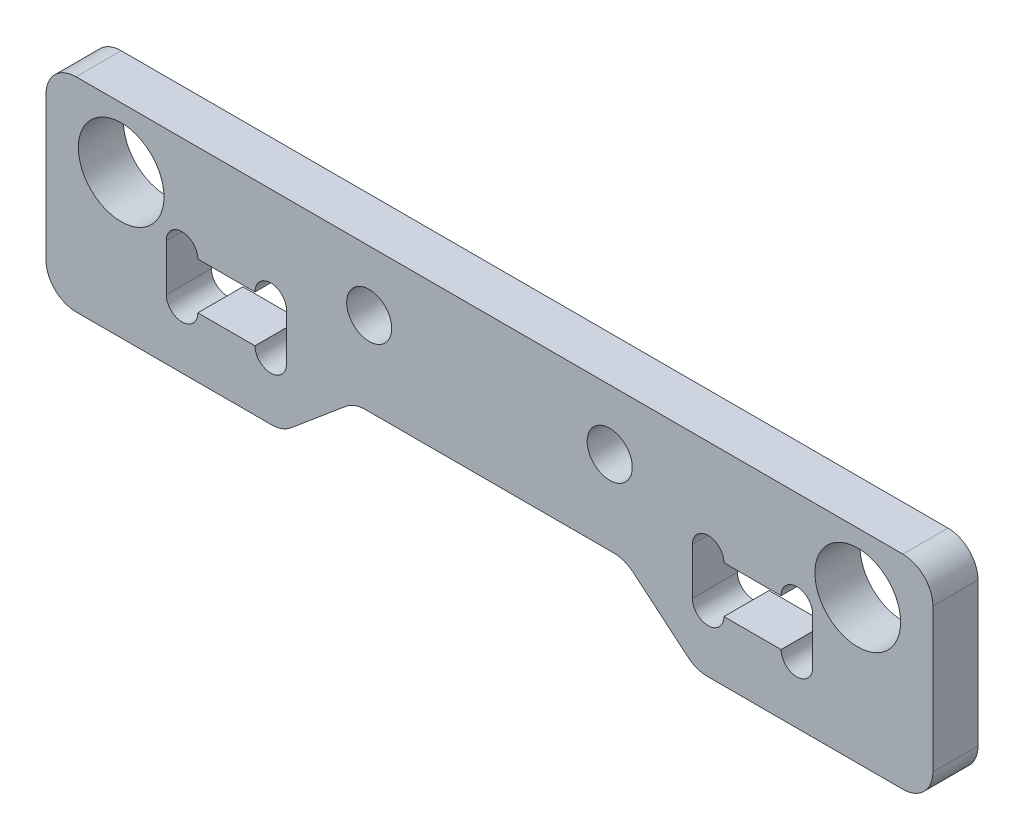
SolidWorks part; units mm, degrees
material "Thornel Mat VMA"
ref_plane "前视基准面" through (0, 0, 0) normal (0, 0, 1) x (1, 0, 0)
ref_plane "上视基准面" through (0, 0, 0) normal (0, 1, 0) x (1, 0, 0)
ref_plane "右视基准面" through (0, 0, 0) normal (1, 0, 0) x (0, 0, -1)
sketch "草图1" plane through (0, 0, 0) normal (0, 0, 1) x (1, 0, 0)
  line L0 (0, 0) -> (0, 24.7592) construction
  line L1 (-29.5, 4) -> (-29.5, -9.55)
  line L8 (-29.5, -9.55) -> (-13.767, -9.55)
  line L11 (29.5, -9.55) -> (29.5, 4)
  line L12 (29.5, 4) -> (-29.5, 4)
  line L13 (13.5, -2.45) -> (21.5, -2.45)
  line L14 (-13.5, -5.55) -> (-21.5, -5.55)
  line L15 (-13.5, -5.55) -> (-13.5, -2.45)
  line L16 (-13.5, -2.45) -> (-21.5, -2.45)
  line L17 (-21.5, -5.55) -> (-21.5, -2.45)
  line L18 (-13.5, -5.55) -> (-21.5, -2.45) construction
  line L19 (-13.5, -2.45) -> (-21.5, -5.55) construction
  line L20 (21.5, -5.55) -> (21.5, -2.45)
  line L21 (13.5, -5.55) -> (21.5, -5.55)
  line L22 (13.5, -5.55) -> (13.5, -2.45)
  line L23 (17.5, -2.45) -> (17.5, -4.5994) construction
  line L24 (-13.767, -9.55) -> (-9, -5.55)
  line L25 (-9, -5.55) -> (9, -5.55)
  line L26 (9, -5.55) -> (13.767, -9.55)
  line L27 (13.767, -9.55) -> (29.5, -9.55)
  circle A0 centre (-24.5, 0) radius 2.85
  circle A1 centre (24.5, 0) radius 2.85
  circle A6 centre (-8, 0) radius 1.5
  circle A7 centre (8, 0) radius 1.5
  circle A8 centre (-20.45, -2.45) radius 1.05
  circle A9 centre (-20.45, -5.55) radius 1.05
  circle A10 centre (-14.55, -2.45) radius 1.05
  circle A11 centre (-14.55, -5.55) radius 1.05
  circle A12 centre (14.55, -2.45) radius 1.05
  circle A13 centre (14.55, -5.55) radius 1.05
  circle A14 centre (20.45, -2.45) radius 1.05
  circle A15 centre (20.45, -5.55) radius 1.05
  point P31 (-17.5, -4)
  dimension "D2" = 5.7
  dimension "D8" = 16
  dimension "D15" = 3
  dimension "D19" = 2.1
  dimension "D1" = 49
  dimension "D9" = 4
  dimension "D10" = 5
  dimension "D11" = 4
  dimension "D16" = 3.1
  dimension "D17" = 8
  dimension "D18" = 35
  dimension "D20" = 4
  dimension "D21" = 18
  dimension "D22" = 40
  dimension "D23" = 4
extrude "凸台-拉伸1" add sketch "草图1" along normal blind 3
fillet "圆角1" radius 2 8 edges at (29.5, 4, 1.5) (13.767, -9.55, 1.5) (9, -5.55, 1.5) (-9, -5.55, 1.5) (-13.767, -9.55, 1.5) (-29.5, 4, 1.5) (-29.5, -9.55, 1.5) (29.5, -9.55, 1.5)
